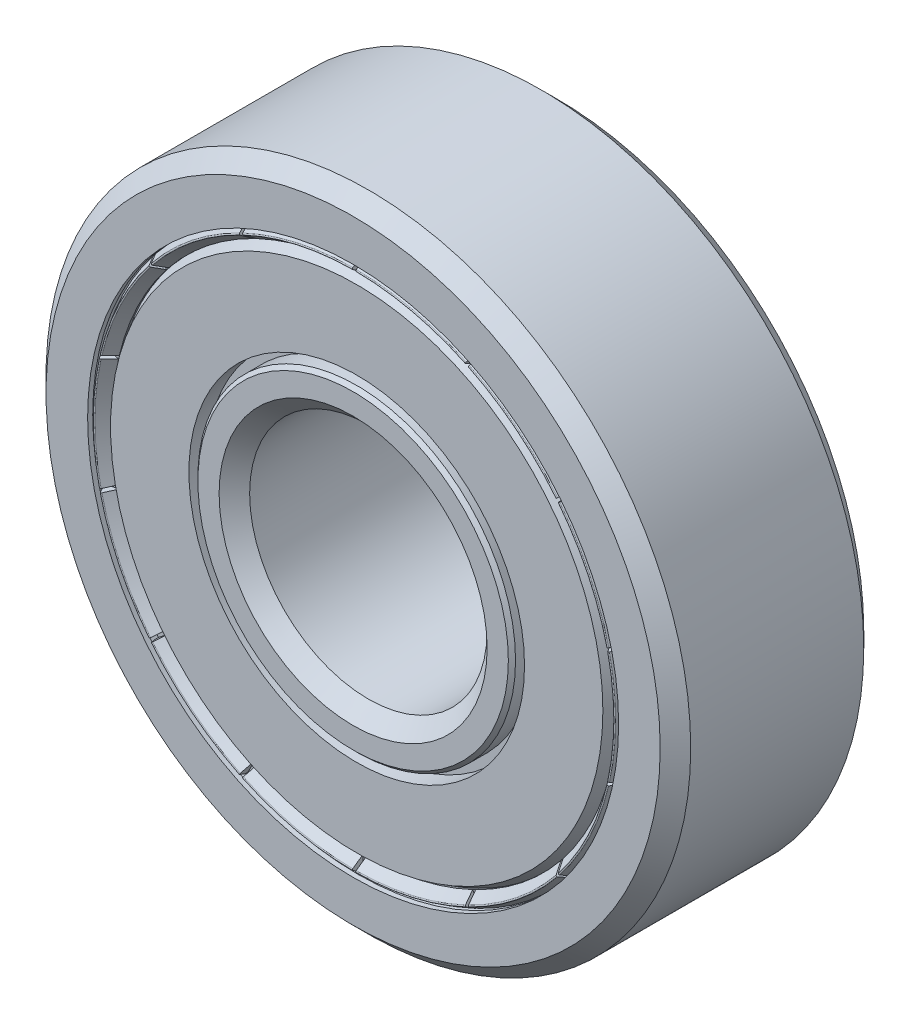
SolidWorks part; units mm, degrees
ref_plane "Front Plane" through (0, 0, 0) normal (0, 0, 1) x (1, 0, 0)
ref_plane "Top Plane" through (0, 0, 0) normal (0, 1, 0) x (1, 0, 0)
ref_plane "Right Plane" through (0, 0, 0) normal (1, 0, 0) x (0, 0, -1)
sketch "Sketch1" plane through (0, 0, 0) normal (0, 0, 1) x (1, 0, 0)
  circle A0 centre (0, 0) radius 3.5
  circle A1 centre (0, 0) radius 9.5
  dimension "OD" = 19
  dimension "ID" = 7
sketch "Sketch2" plane through (0, 0, 0) normal (1, 0, 0) x (0, 0, -1)
  line L0 (-3, 9.5) -> (3, 9.5)
  line L1 (-3, 3.5) -> (-3, -3.5) construction
  line L2 (3, 9.5) -> (3, -9.5) construction
  line L3 (-3, 0) -> (3, 0) construction
  line L6 (0, 9.5) -> (0, 3.5) construction
  circle A0 centre (0, 6.5) radius 2.1 construction
  point P8 (0, 9.5)
  dimension "Approx. Ball Dia." = 4.2
  dimension "Width" = 6
  dimension "For Shaft Diameter" = 7
  dimension "For Housing ID" = 19
sketch "Sketch3" plane through (0, 0, 0) normal (1, 0, 0) x (0, 0, -1)
  line L0 (0, 0) -> (0, 7) construction
  line L1 (-3, 3.5) -> (-3, -3.5) construction
  line L2 (2.55, 9.5) -> (-2.55, 9.5)
  line L3 (-2.55, 9.5) -> (-3, 9.05)
  line L4 (-3, 9.05) -> (-3, 7.8252)
  line L5 (-3, 7.8252) -> (-2.85, 7.8252)
  line L6 (-2.85, 7.8252) -> (-2.85, 8.2126)
  line L7 (-2.85, 8.2126) -> (-2.7439, 8.3187)
  line L8 (-2.7439, 8.3187) -> (-1.05, 8.3187)
  line L10 (-3, 9.5) -> (3, 9.5) construction
  line L12 (-2.85, 8.2126) -> (-2.85, 8.6) construction
  line L13 (2.7439, 8.3187) -> (1.05, 8.3187)
  line L14 (2.85, 8.2126) -> (2.7439, 8.3187)
  line L15 (2.85, 7.8252) -> (2.85, 8.2126)
  line L16 (3, 7.8252) -> (2.85, 7.8252)
  line L17 (3, 9.05) -> (3, 7.8252)
  line L18 (2.55, 9.5) -> (3, 9.05)
  line L19 (2.55, 3.5) -> (-2.55, 3.5)
  line L20 (-2.55, 3.5) -> (-3, 3.95)
  line L21 (-3, 3.95) -> (-3, 4.5753)
  line L22 (-3, 4.5753) -> (-2.8939, 4.6813)
  line L23 (-2.8939, 4.6813) -> (-1.05, 4.6813)
  line L25 (2.8939, 4.6813) -> (1.05, 4.6813)
  line L26 (3, 4.5753) -> (2.8939, 4.6813)
  line L27 (3, 3.95) -> (3, 4.5753)
  line L28 (2.55, 3.5) -> (3, 3.95)
  circle A2 centre (0, 6.5) radius 2.1 construction
  arc A3 (-1.05, 8.3187) -> (1.05, 8.3187) centre (0, 6.5) cw
  arc A4 (-1.05, 4.6813) -> (1.05, 4.6813) centre (0, 6.5) ccw
  point P5 (0, 8.6)
  point P31 (0, 9.5)
  point P37 (0, 3.5)
  dimension "D1" = 45
  dimension "D2" = 0.15
  dimension "D3" = 2.1
  dimension "D4" = 0.45
revolve "Revolve1" add sketch "Sketch3" angle 360 about L3
sketch "Sketch4" plane through (0, 0, 0) normal (1, 0, 0) x (0, 0, -1)
  line L0 (0, 8.6) -> (0, 4.4)
  line L1 (0, 9.5) -> (0, 3.5) construction
  circle A0 centre (0, 6.5) radius 2.1 construction
  arc A1 (0, 4.4) -> (0, 8.6) centre (0, 6.5) cw
revolve "Revolve2" add sketch "Sketch4" angle 360 about L6
pattern_circular "CirPattern1" count 7 over 360 about axis through (0, 0, 0) along (0, 0, 1) of bodies 106
sketch "Sketch5" plane through (0, 0, 0) normal (1, 0, 0) x (0, 0, -1)
  line L0 (-2.1, 6.5) -> (-2.1, 4.6813) construction
  line L1 (-2.8939, 4.6813) -> (-1.05, 4.6813) construction
  line L3 (-2.1, 4.6813) -> (-2.3646, 4.6813)
  line L4 (-2.3646, 4.6813) -> (-2.3646, 4.946)
  line L5 (-2.3646, 4.946) -> (-2.8939, 4.946)
  line L6 (-2.8939, 4.946) -> (-2.8939, 7.2549)
  line L7 (-2.8939, 7.2549) -> (-2.3646, 7.5605)
  line L8 (-2.3646, 7.5605) -> (-2.1, 7.5605)
  line L9 (-2.1, 7.5605) -> (-2.1, 4.6813)
  line L10 (0, 6.5) -> (0, 9.5) construction
  line L11 (2.3646, 7.5605) -> (2.1, 7.5605)
  line L12 (2.8939, 7.2549) -> (2.3646, 7.5605)
  line L13 (2.8939, 4.946) -> (2.8939, 7.2549)
  line L14 (2.3646, 4.946) -> (2.8939, 4.946)
  line L15 (2.3646, 4.6813) -> (2.3646, 4.946)
  line L16 (2.1, 4.6813) -> (2.3646, 4.6813)
  line L17 (2.1, 7.5605) -> (2.1, 4.6813)
  line L18 (-2.8939, 7.2549) -> (-2.6293, 7.2549) construction
  line L19 (-2.6293, 7.2549) -> (-2.3646, 7.2549) construction
  line L20 (-2.3646, 7.2549) -> (-2.1, 7.2549) construction
  line L21 (-2.3646, 7.5605) -> (-2.3646, 7.8252) construction
  circle A0 centre (0, 6.5) radius 2.1 construction
  dimension "D1" = 30
revolve "Revolve3" add sketch "Sketch5" angle 360 about L3
sketch "Sketch6" plane through (0, 0, 0) normal (1, 0, 0) x (0, 0, -1)
  line L0 (-2.5667, 7.8252) -> (-2.7375, 7.8252)
  line L1 (-2.7375, 7.8252) -> (-3, 7.6736)
  line L2 (-3, 7.6736) -> (-2.6567, 7.4333)
  line L4 (-2.8939, 7.2549) -> (-2.3646, 7.5605) construction
  line L5 (-2.5667, 7.4438) -> (-2.5667, 7.8252)
  line L6 (-3, 7.8252) -> (-2.85, 7.8252) construction
  line L7 (-2.6567, 7.4333) -> (-2.6267, 7.4333)
  line L8 (-2.6267, 7.4333) -> (-2.5667, 7.4438)
  line L9 (-3, 9.05) -> (-3, -9.05) construction
  line L11 (-2.6267, 7.4333) -> (-2.5967, 7.4333) construction
  line L12 (-2.5967, 7.4333) -> (-2.5667, 7.4333) construction
  point P27 (-2.6521, 7.8252)
  dimension "D1" = 30
  dimension "D3" = 10
  dimension "D2" = 35
  dimension "D4" = 0.03
  dimension "D5" = 0.2625
revolve "Revolve4" add sketch "Sketch6" angle 360 about L3
fillet "Fillet1" radius 0.03 1 edges at (7.6736, 0, 3)
sketch "Sketch7" plane through (0, 0, 0) normal (0, 0, 1) x (1, 0, 0)
  line L0 (-0.05, 7.8252) -> (-0.05, 7.9252)
  line L1 (-0.05, 7.8252) -> (0.05, 7.8252) construction
  line L2 (-0.05, 7.8252) -> (-0.05, 7.4333)
  line L3 (-0.05, 7.4333) -> (0.05, 7.4333) construction
  line L4 (0.05, 7.8252) -> (0.05, 7.4333)
  line L5 (-0.05, 7.9252) -> (0.05, 7.9252)
  line L6 (0.05, 7.9252) -> (0.05, 7.8252)
  line L7 (-0.05, 7.4333) -> (-0.05, 7.3333)
  line L8 (-0.05, 7.3333) -> (0.05, 7.3333)
  line L9 (0.05, 7.3333) -> (0.05, 7.4333)
  dimension "D1" = 0.1
extrude "Cut-Extrude1" cut sketch "Sketch7" along normal through all from vertex at 2.6521 starting at point (0, 7.8252, 2.6521)
pattern_circular "CirPattern2" count 14 over 360 about axis through (0, 0, 3) along (0, 0, -1) of "Cut-Extrude1"
mirror "Mirror1" about plane through (0, 0, 0) normal (0, 0, 1) of bodies 120
equation "\"Approx. Ball Dia.@Sketch2\"=( \"OD@Sketch1\" - \"ID@Sketch1\" )  * .5 * .7"
equation "\"D2@Sketch3\"=\"Width@Sketch2\"*.025"
equation "\"D3@Sketch3\"=\"Approx. Ball Dia.@Sketch2\"*.5"
equation "\"D4@Sketch3\"=\"Width@Sketch2\"*.075"
equation "\"Approx No of Balls\"= ( pi * \"OD@Sketch1\" ) * .5 / \"Approx. Ball Dia.@Sketch2\""
equation "\"D1@CirPattern1\"=\"Approx No of Balls\""
equation "\"D4@Sketch6\"=\"D2@Sketch3\"*.2"
equation "\"D1@CirPattern2\"=\"Approx No of Balls\"*2"
equation "\"D5@Sketch6\"=\"D2@Sketch3\"*1.75"
equation "\"D1@Fillet1\"=\"d4@sketch6\""
